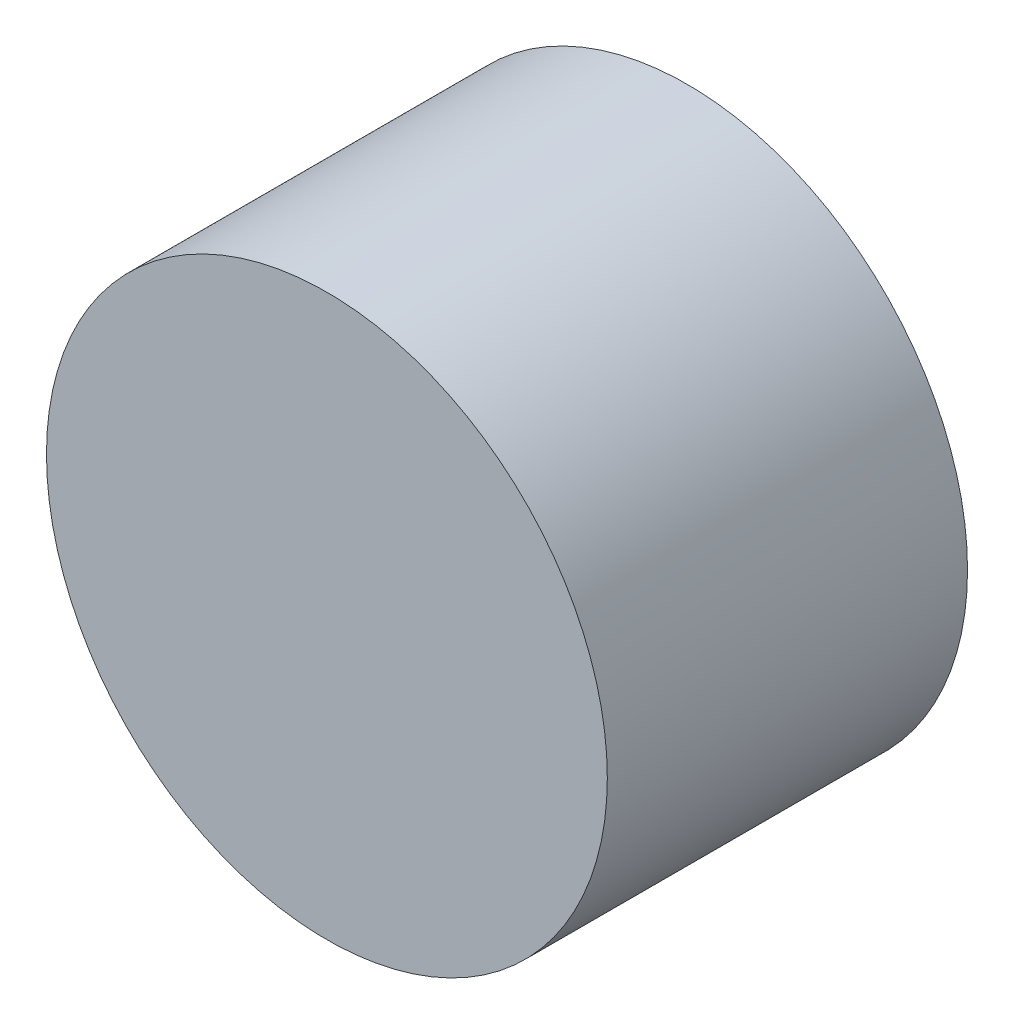
SolidWorks part; units mm, degrees
ref_plane "Front Plane" through (0, 0, 0) normal (0, 0, 1) x (1, 0, 0)
ref_plane "Top Plane" through (0, 0, 0) normal (0, 1, 0) x (1, 0, 0)
ref_plane "Right Plane" through (0, 0, 0) normal (1, 0, 0) x (0, 0, -1)
sketch "Sketch1" plane through (0, 0, 0) normal (0, 0, 1) x (1, 0, 0)
  circle A0 centre (0, 0) radius 51.4142
extrude "Boss-Extrude1" add sketch "Sketch1" along normal blind 66.04
